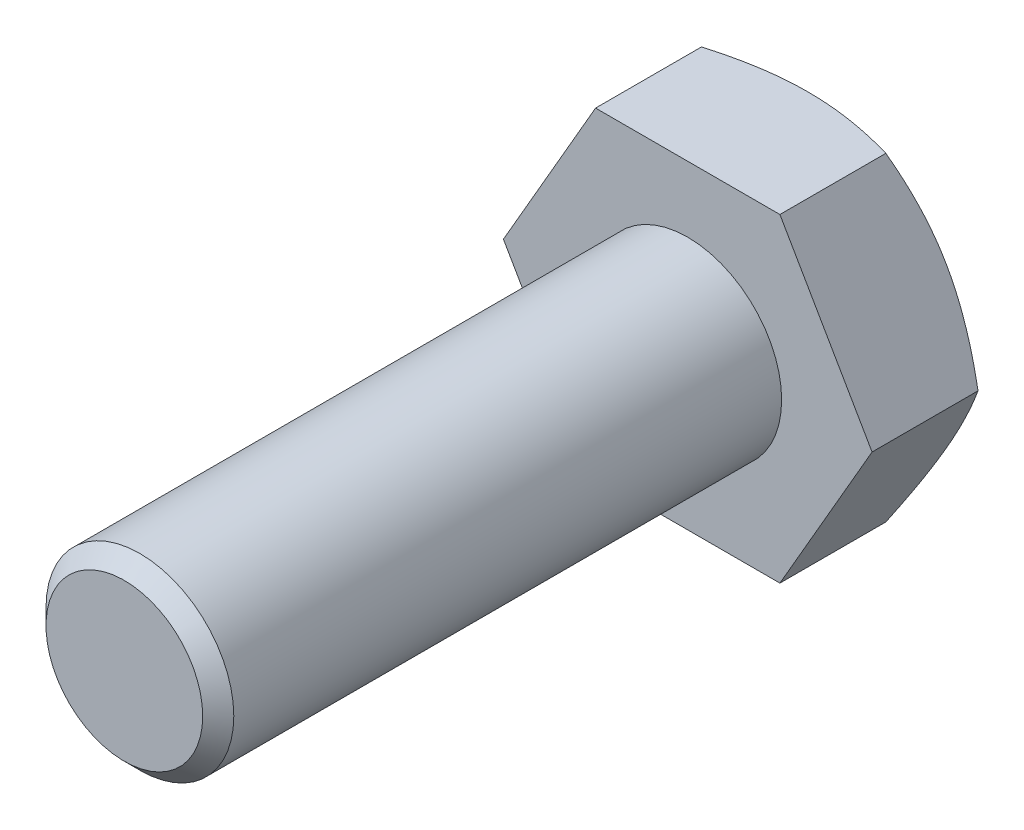
SolidWorks part; units mm, degrees
material "Простая углеродистая сталь"
ref_plane "Спереди" through (0, 0, 0) normal (0, 0, 1) x (1, 0, 0)
ref_plane "Сверху" through (0, 0, 0) normal (0, 1, 0) x (1, 0, 0)
ref_plane "Справа" through (0, 0, 0) normal (1, 0, 0) x (0, 0, -1)
sketch "Эскиз1" plane through (0, 0, 0) normal (0, 0, 1) x (1, 0, 0)
  line L1 (-4.9075, 8.5) -> (-9.815, 0)
  line L2 (-9.815, 0) -> (-4.9075, -8.5)
  line L3 (-4.9075, -8.5) -> (4.9075, -8.5)
  line L4 (4.9075, -8.5) -> (9.815, 0)
  line L5 (9.815, 0) -> (4.9075, 8.5)
  line L6 (4.9075, 8.5) -> (-4.9075, 8.5)
  circle A0 centre (0, 0) radius 8.5 construction
  dimension "D1" = 17
extrude "Бобышка-Вытянуть1" add sketch "Эскиз1" along normal blind 6.4
sketch "Эскиз2" plane through (0, 0, 6.4) normal (0, 0, 1) x (1, 0, 0)
  circle A0 centre (0, 0) radius 5
  dimension "D1" = 10
extrude "Бобышка-Вытянуть2" add sketch "Эскиз2" along normal blind 30
cosmetic thread "Условное изображение резьбы1" parameters "D1"=15, "D2"=8.344
sketch "Эскиз3" plane through (0, 0, 0) normal (1, 0, 0) x (0, 0, -1)
  line L0 (0, 8.5) -> (0, 11.5)
  line L1 (0, 11.5) -> (-1.7321, 11.5)
  line L2 (-1.7321, 11.5) -> (0, 8.5)
  line L3 (-1000, 0) -> (49000, 0) construction
  dimension "D1" = 30
  dimension "D2" = 3
revolve "Вырез-Повернуть1" cut sketch "Эскиз3" angle 360 about L3
chamfer "Фаска1" distance 0.828 angle 45 1 edges at (5, 0, 36.4)
